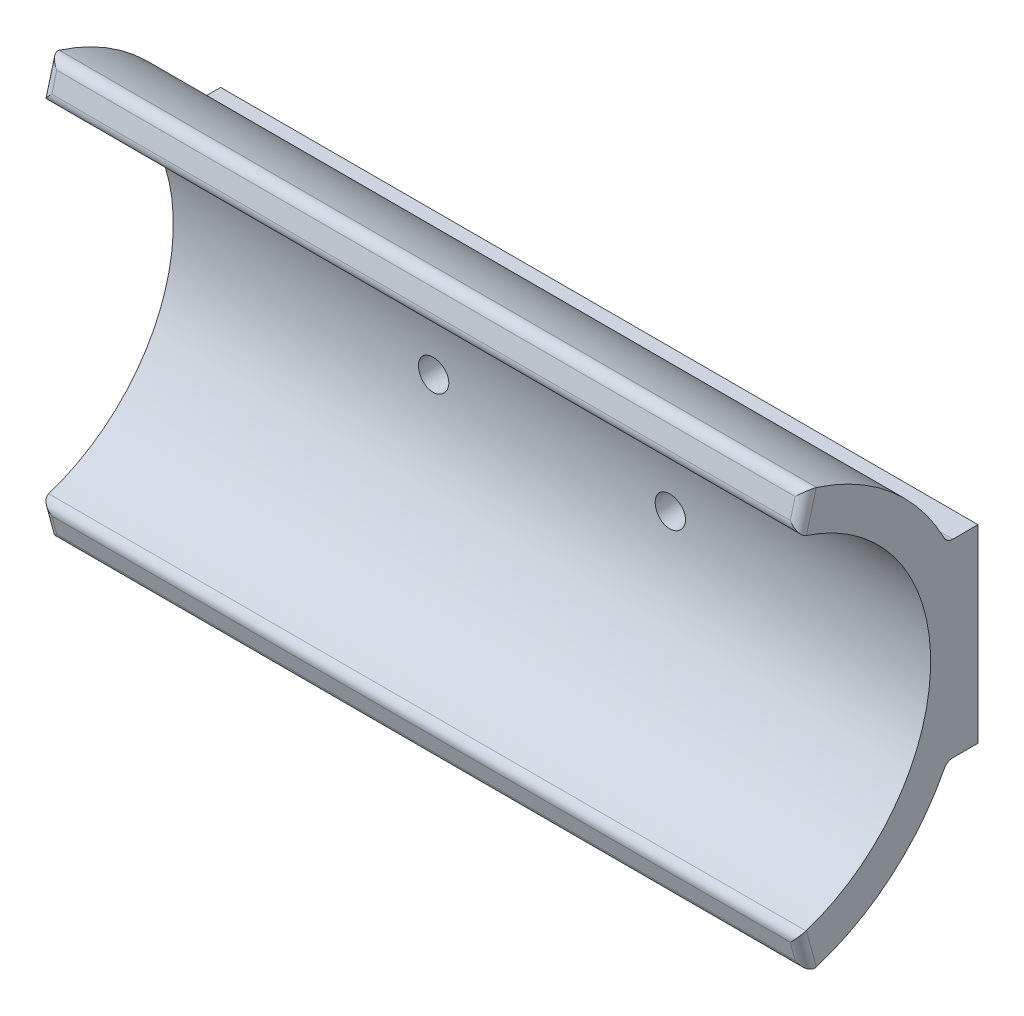
SolidWorks part; units mm, degrees
ref_plane "Front Plane" through (0, 0, 0) normal (1, 0, 0) x (0, 1, 0)
ref_plane "Top Plane" through (0, 0, 0) normal (0, 0, 1) x (0, 1, 0)
ref_plane "Right Plane" through (0, 0, 0) normal (0, 1, 0) x (-1, 0, 0)
sketch "Sketch1" plane through (0, 0, 0) normal (1, 0, 0) x (0, 1, 0)
  line L0 (18.3526, -4.9176) -> (22.2163, -5.9528)
  line L1 (-18.3526, -4.9176) -> (-22.2163, -5.9528)
  line L2 (0, 0) -> (57.6225, -15.4399) construction
  line L3 (0, 0) -> (38.6244, 0) construction
  line L4 (0, 0) -> (-49.8321, -13.3525) construction
  line L7 (-10, -20.7123) -> (-10, -24)
  line L8 (-10, -24) -> (10, -24)
  line L9 (10, -20.7123) -> (10, -24)
  line L10 (-10, -19) -> (10, -24) construction
  line L11 (-10, -24) -> (10, -19) construction
  arc A0 (-18.3526, -4.9176) -> (18.3526, -4.9176) centre (0, 0) ccw
  arc A1 (-22.2163, -5.9528) -> (-10, -20.7123) centre (0, 0) ccw
  arc A2 (10, -20.7123) -> (22.2163, -5.9528) centre (0, 0) ccw
  point P12 (0, -21.5)
  dimension "D1" = 19
  dimension "D2" = 23
  dimension "D3" = 5
  dimension "D4" = 15
  dimension "D5" = 15
  dimension "D6" = 20
  dimension "D7" = 24
extrude "Boss-Extrude1" add sketch "Sketch1" along normal mid plane 80
sketch "Sketch2" plane through (0, 0, -24) normal (0, 0, -1) x (-1, 0, 0)
  line L0 (0, 0) -> (0, 14.4324) construction
  circle A0 centre (12.5, 0) radius 1.6
  circle A1 centre (-12.5, 0) radius 1.6
  dimension "D2" = 3.2
  dimension "D1" = 12.5
extrude "Cut-Extrude1" cut sketch "Sketch2" against normal through all both and the other way through all
fillet "Fillet1" radius 1 10 edges at (0, 22.2163, -5.9528) (40, 20.2844, -5.4352) (0, 18.3526, -4.9176) (-40, 20.2844, -5.4352) (0, -18.3526, -4.9176) (40, -20.2844, -5.4352) (0, -22.2163, -5.9528) (-40, -20.2844, -5.4352) (0, 10, -20.7123) (0, -10, -20.7123)
